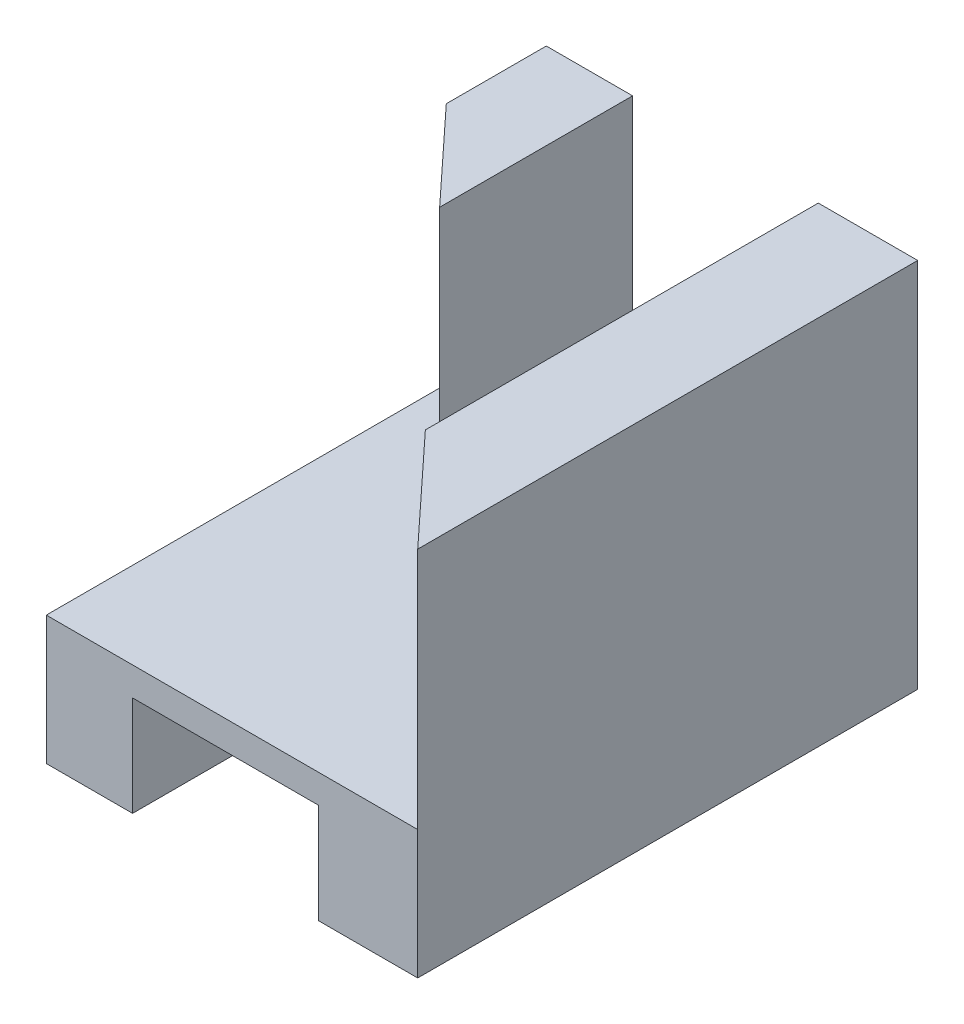
SolidWorks part; units mm, degrees
ref_plane "前基準面" through (0, 0, 0) normal (0, 0, 1) x (1, 0, 0)
ref_plane "上基準面" through (0, 0, 0) normal (0, 1, 0) x (1, 0, 0)
ref_plane "右基準面" through (0, 0, 0) normal (1, 0, 0) x (0, 0, -1)
sketch "草圖1" plane through (0, 0, 0) normal (0, 0, 1) x (1, 0, 0)
  line L0 (-6.9589, 13) -> (-6.9589, 0)
  line L1 (-13, 13) -> (-6.9589, 13)
  line L2 (-13, 13) -> (-13, -13)
  line L3 (-13, -13) -> (-6.9589, -13)
  line L4 (13, 13) -> (13, -13)
  line L5 (-13, 13) -> (13, -13) construction
  line L6 (-13, -13) -> (13, 13) construction
  line L7 (-6.9589, 0) -> (6.0411, 0)
  line L8 (6.0411, 0) -> (6.0411, 13)
  line L9 (-6.9589, -13) -> (-6.9589, -6)
  line L10 (-6.9589, -6) -> (6.0411, -6)
  line L11 (6.0411, -6) -> (6.0411, -13)
  line L12 (6.0411, 13) -> (13, 13)
  line L13 (6.0411, -13) -> (13, -13)
  point P0 (0, 0)
  dimension "D1" = 26
  dimension "D2" = 13
  dimension "D3" = 13
  dimension "D4" = 7
  dimension "D5" = 26
  dimension "D6" = 13
extrude "填料-伸長1" add sketch "草圖1" along normal blind 35
sketch "草圖2" plane through (0, 13, 0) normal (0, 1, 0) x (1, 0, 0)
  line L0 (-13, 0) -> (-13, -7)
  line L1 (-13, -35) -> (-13, 0) construction
  line L2 (-13, -7) -> (13, -35)
  line L3 (13, -35) -> (-13, -35)
  line L4 (-13, -35) -> (-13, -7)
  line M3 (-13, 0) -> (-13, -35)
  line M4 (-13, -35) -> (-6.9589, -35)
  line M5 (-6.9589, -35) -> (-6.9589, 0)
  dimension "D1" = 7
extrude "除料-伸長1" cut sketch "草圖2" against normal blind 17 contours L3 L2 M5 | L2 M3 M4 M5
